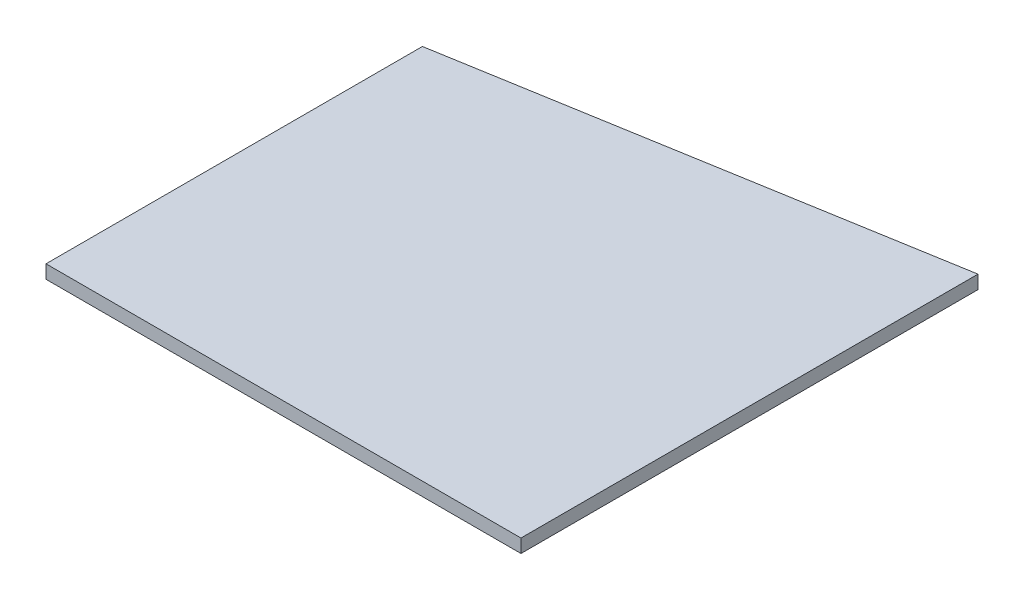
SolidWorks part; units mm, degrees
ref_plane "Front Plane" through (0, 0, 0) normal (0, 0, 1) x (1, 0, 0)
ref_plane "Top Plane" through (0, 0, 0) normal (0, 1, 0) x (1, 0, 0)
ref_plane "Right Plane" through (0, 0, 0) normal (1, 0, 0) x (0, 0, -1)
sketch "Sketch1" plane through (0, 0, 0) normal (0, 1, 0) x (1, 0, 0)
  line L0 (21.1004, 24.7124) -> (21.1004, -26.2876)
  line L1 (21.1004, -26.2876) -> (-31.8996, -26.2876)
  line L2 (-31.8996, -26.2876) -> (-31.8996, 15.7124)
  line L3 (-31.8996, 15.7124) -> (21.1004, 24.7124)
  dimension "D1" = 51
  dimension "D2" = 53
  dimension "D3" = 42
extrude "Boss-Extrude1" add sketch "Sketch1" along normal blind 1.5
